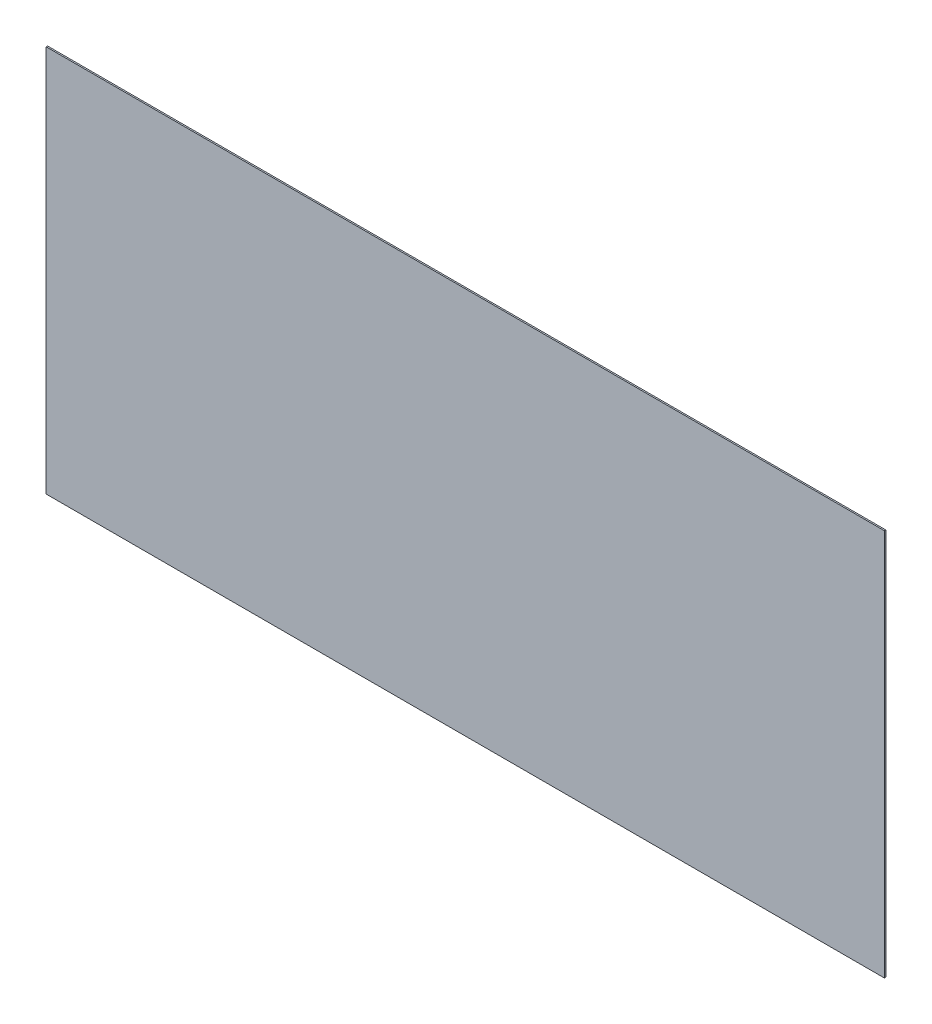
SolidWorks part; units mm, degrees
ref_plane "Front Plane" through (0, 0, 0) normal (0, 0, 1) x (1, 0, 0)
ref_plane "Top Plane" through (0, 0, 0) normal (0, 1, 0) x (1, 0, 0)
ref_plane "Right Plane" through (0, 0, 0) normal (1, 0, 0) x (0, 0, -1)
sketch "Sketch1" plane through (0, 0, 0) normal (0, 0, 1) x (1, 0, 0)
  line L1 (16, 35.25) -> (75.5, 35.25)
  line L2 (16, 35.25) -> (16, 7.75)
  line L3 (16, 7.75) -> (75.5, 7.75)
  line L4 (75.5, 35.25) -> (75.5, 7.75)
  line L6 (16.5, 24) -> (16.5, 34) construction
  line L7 (75, 34) -> (75, 24) construction
  arc A2 (18, 34) -> (16.5, 34) centre (17.25, 34) ccw construction
  arc A3 (16.5, 9) -> (18, 9) centre (17.25, 9) ccw construction
  dimension "D1" = 0.5
  dimension "D2" = 1.25
  dimension "D3" = 0.5
  dimension "D4" = 1.25
extrude "Extrude1" add sketch "Sketch1" along normal blind 0.1
